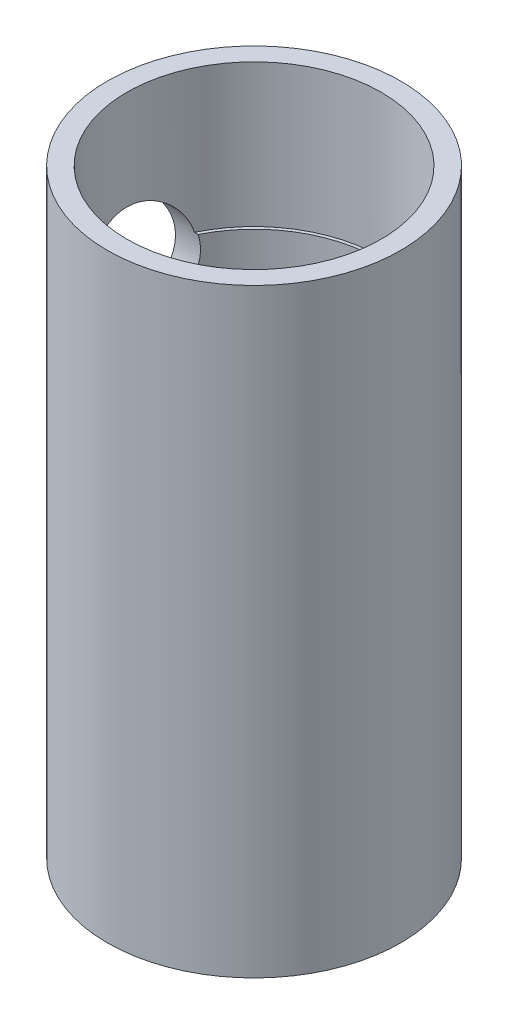
SolidWorks part; units mm, degrees
ref_plane "Front Plane" through (0, 0, 0) normal (0, 0, 1) x (1, 0, 0)
ref_plane "Top Plane" through (0, 0, 0) normal (0, 1, 0) x (1, 0, 0)
ref_plane "Right Plane" through (0, 0, 0) normal (1, 0, 0) x (0, 0, -1)
sketch "Sketch1" plane through (0, 0, 0) normal (0, 1, 0) x (1, 0, 0)
  line L0 (0, 38.25) -> (0, 45.25) construction
  circle A0 centre (0, 0) radius 38.25
  circle A1 centre (0, 0) radius 45.25
  dimension "D1" = 76.5
  dimension "D2" = 7
extrude "Boss-Extrude1" add sketch "Sketch1" along normal mid plane 185
sketch "Sketch2" plane through (0, -92.5, 0) normal (0, -1, 0) x (1, 0, 0)
  line L0 (0, 36.25) -> (0, 38.25) construction
  circle A0 centre (0, 0) radius 36.25
  circle A1 centre (0, 0) radius 38.25 construction
  circle A2 centre (0, 0) radius 38.25
  dimension "D1" = 2
extrude "Boss-Extrude2" add sketch "Sketch2" against normal blind 100 from offset 6.35 offset against normal yes
sketch "Sketch6" plane through (0, 92.5, 0) normal (0, 1, 0) x (1, 0, 0)
  line L0 (0, 38.25) -> (0, 39.25) construction
  circle A0 centre (0, 0) radius 39.25
  circle A1 centre (0, 0) radius 38.25 construction
  circle A2 centre (0, 0) radius 38.25
  dimension "D1" = 1
extrude "Cut-Extrude3" cut sketch "Sketch6" against normal blind 44
sketch "Sketch7" plane through (0, 0, 0) normal (1, 0, 0) x (0, 0, -1)
  line L0 (45.25, 92.5) -> (-45.25, 92.5) construction
  circle A0 centre (0, 44.35) radius 17.5
  dimension "D2" = 35
  dimension "D1" = 48.15
extrude "Cut-Extrude4" cut sketch "Sketch7" against normal through all
